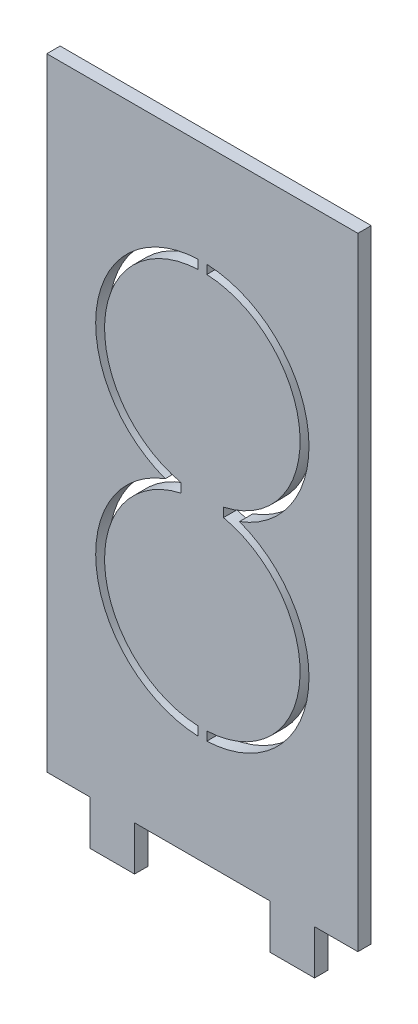
SolidWorks part; units mm, degrees
material "Glas"
ref_plane "Ebene vorne" through (0, 0, 0) normal (0, 0, 1) x (1, 0, 0)
ref_plane "Ebene oben" through (0, 0, 0) normal (0, 1, 0) x (1, 0, 0)
ref_plane "Ebene rechts" through (0, 0, 0) normal (1, 0, 0) x (0, 0, -1)
sketch "Skizze1" plane through (0, 0, 0) normal (0, 0, 1) x (1, 0, 0)
  line L1 (0, 0) -> (35, 0)
  line L2 (0, 0) -> (0, 75)
  line L3 (0, 75) -> (35, 75)
  line L4 (35, 0) -> (35, 75)
  dimension "D1" = 35
  dimension "D2" = 75
extrude "Aufsatz-Linear austragen1" add sketch "Skizze1" along normal blind 1.5
sketch "Skizze3" plane through (0, 0, 1.5) normal (0, 0, 1) x (1, 0, 0)
  line L0 (0, 0) -> (35, 0) construction
  line L1 (9.875, 0) -> (25.125, 0)
  line L2 (9.875, 0) -> (9.875, 5)
  line L3 (9.875, 5) -> (25.125, 5)
  line L4 (25.125, 0) -> (25.125, 5)
  line L5 (35, 0) -> (35, 75) construction
  line L6 (30.125, 5) -> (35, 5)
  line L7 (30.125, 5) -> (30.125, 0)
  line L8 (30.125, 0) -> (35, 0)
  line L9 (35, 5) -> (35, 0)
  line L10 (4.875, 5) -> (0, 5)
  line L11 (4.875, 5) -> (4.875, 0)
  line L12 (4.875, 0) -> (0, 0)
  line L13 (0, 5) -> (0, 0)
  dimension "D1" = 4.875
  dimension "D2" = 4.875
  dimension "D3" = 0
  dimension "D4" = 5
  dimension "D5" = 5
  dimension "D6" = 5
  dimension "D7" = 5
extrude "Schnitt-Linear austragen12" cut sketch "Skizze3" against normal blind 20
sketch "Skizze13" plane through (0, 0, 1.5) normal (0, 0, 1) x (1, 0, 0)
  line L0 (15.1175, 40.7611) -> (15.1175, 39.7389)
  line L5 (25.125, 5) -> (9.875, 5) construction
  line L6 (35, 5) -> (35, 75) construction
  line L7 (35, 75) -> (0, 75) construction
  line L8 (19.8825, 40.7611) -> (19.8825, 39.7389)
  arc A13 (19.8825, 40.7611) -> (15.1175, 40.7611) centre (17.5, 51.5) ccw
  arc A14 (21.6745, 40.2495) -> (13.3255, 40.2495) centre (17.5, 51.5) ccw
  arc A15 (21.6745, 40.2495) -> (13.3255, 40.2495) centre (17.5, 29) cw
  arc A16 (19.8825, 39.7389) -> (15.1175, 39.7389) centre (17.5, 29) cw
  point P16 (13.3255, 40.2494)
  dimension "D3" = 24
  dimension "D4" = 17.5
  dimension "D7" = 23.5
extrude "Schnitt-Linear austragen18" cut sketch "Skizze13" against normal blind 1.5
sketch "Skizze14" plane through (0, 0, 1.5) normal (0, 0, 1) x (1, 0, 0)
  line L0 (35, 5) -> (35, 75) construction
  line L1 (17, 68.1857) -> (18, 68.1857)
  line L2 (17, 68.1857) -> (17, 10.8736)
  line L3 (17, 10.8736) -> (18, 10.8736)
  line L4 (18, 68.1857) -> (18, 10.8736)
  dimension "D1" = 1
  dimension "D2" = 17
extrude "Aufsatz-Linear austragen2" add sketch "Skizze14" against normal blind 1.5
